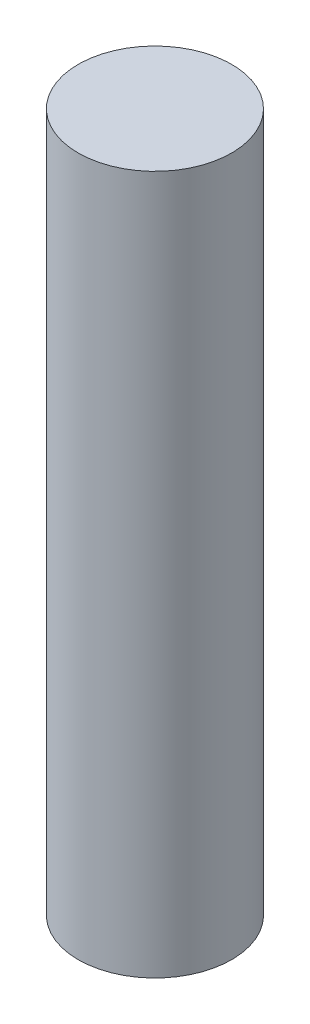
SolidWorks part; units mm, degrees
ref_plane "Front Plane" through (0, 0, 0) normal (0, 0, 1) x (1, 0, 0)
ref_plane "Top Plane" through (0, 0, 0) normal (0, 1, 0) x (1, 0, 0)
ref_plane "Right Plane" through (0, 0, 0) normal (1, 0, 0) x (0, 0, -1)
sketch "Sketch1" plane through (0, 0, 0) normal (0, 1, 0) x (1, 0, 0)
  circle A0 centre (0, 0) radius 40
extrude "Boss-Extrude1" add sketch "Sketch1" along normal blind 364
sketch "Sketch2" plane through (0, 0, 0) normal (0, -1, 0) x (1, 0, 0)
  circle A0 centre (0, 0) radius 16
